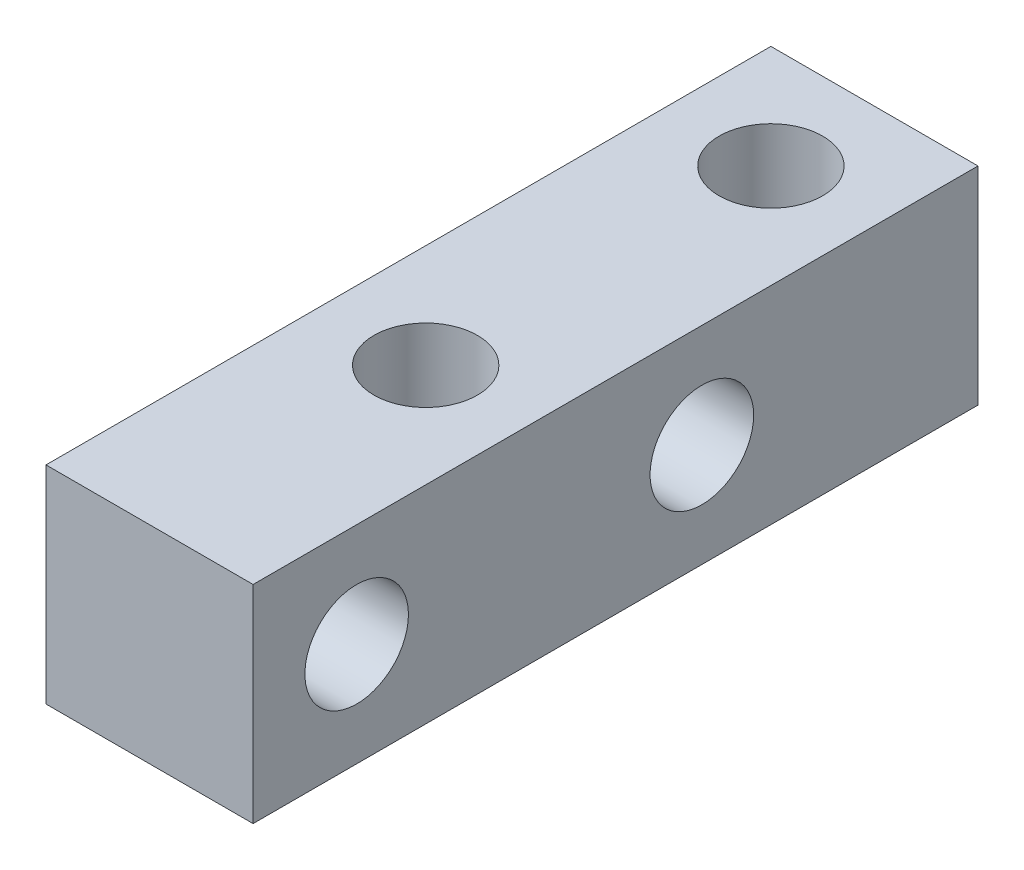
SolidWorks part; units mm, degrees
material "6061-T4 (SS)"
ref_plane "前视基准面" through (0, 0, 0) normal (0, 0, 1) x (1, 0, 0)
ref_plane "上视基准面" through (0, 0, 0) normal (0, 1, 0) x (1, 0, 0)
ref_plane "右视基准面" through (0, 0, 0) normal (1, 0, 0) x (0, 0, -1)
other "Configuration Table"
sketch "草图1" plane through (0, 0, 0) normal (0, 0, 1) x (1, 0, 0)
  line L1 (-3, -3) -> (3, -3)
  line L2 (-3, -3) -> (-3, 3)
  line L3 (-3, 3) -> (3, 3)
  line L4 (3, -3) -> (3, 3)
  line L5 (-3, -3) -> (3, 3) construction
  line L6 (-3, 3) -> (3, -3) construction
  point P0 (0, 0)
  dimension "D1" = 6
extrude "凸台-拉伸1" add sketch "草图1" along normal blind 21
sketch "草图2" plane through (0, 3, 0) normal (0, 1, 0) x (1, 0, 0)
  line L0 (0, 0) -> (0, -3) construction
  line L1 (0, -3) -> (0, -13) construction
  circle A0 centre (0, -3) radius 1.5
  circle A1 centre (0, -13) radius 1.5
  dimension "D3" = 3
  dimension "D1" = 3
  dimension "D2" = 10
extrude "切除-拉伸1" cut sketch "草图2" against normal up to surface (6 mm away) up to face at (0, -3, 10.5)
sketch "草图3" plane through (3, 0, 0) normal (1, 0, 0) x (0, 0, -1)
  line L0 (-21, 0) -> (-18, 0) construction
  line L1 (-21, -3) -> (-21, 3) construction
  line L2 (-18, 0) -> (-8, 0) construction
  circle A0 centre (-18, 0) radius 1.5
  circle A1 centre (-8, 0) radius 1.5
  dimension "D3" = 3
  dimension "D1" = 10
  dimension "D2" = 3
extrude "切除-拉伸2" cut sketch "草图3" against normal up to surface (6 mm away) up to face at (-3, 0, 10.5)
